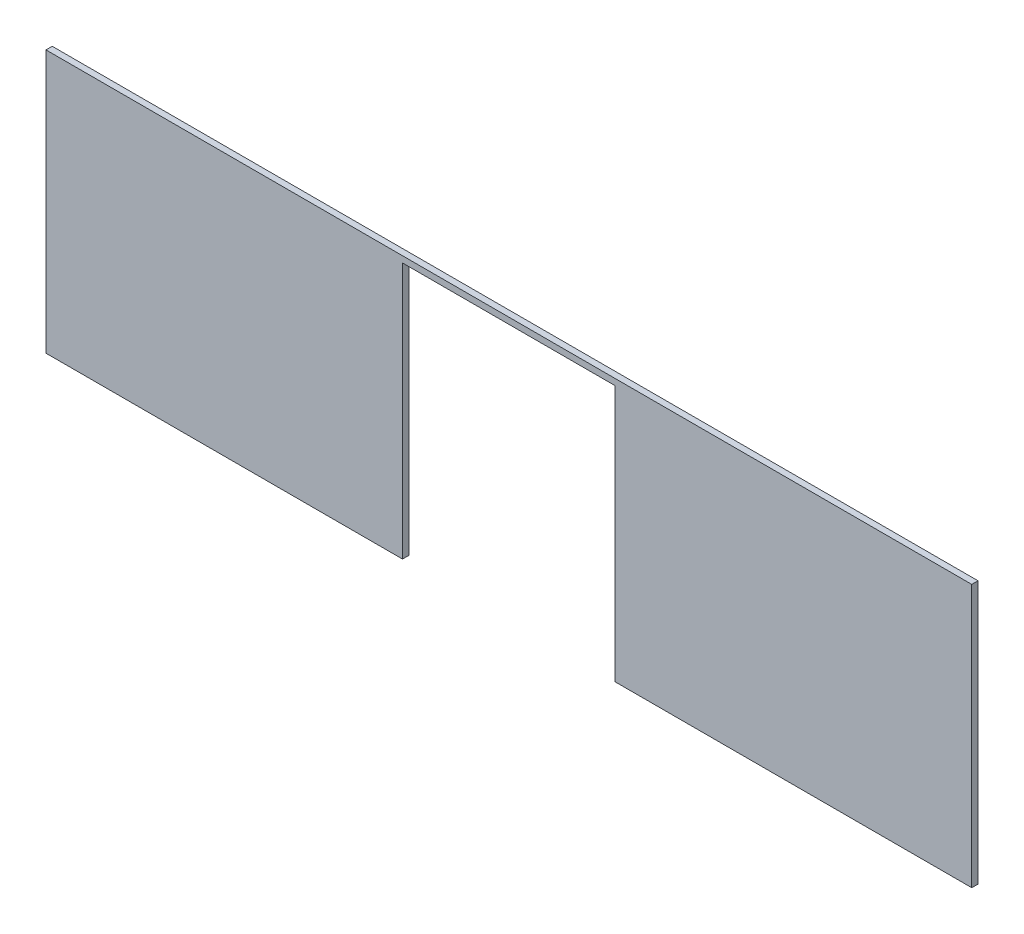
SolidWorks part; units mm, degrees
ref_plane "Front Plane" through (0, 0, 0) normal (0, 0, 1) x (1, 0, 0)
ref_plane "Top Plane" through (0, 0, 0) normal (0, 1, 0) x (1, 0, 0)
ref_plane "Right Plane" through (0, 0, 0) normal (1, 0, 0) x (0, 0, -1)
sketch "Sketch1" plane through (0, 0, 0) normal (0, 0, 1) x (1, 0, 0)
  line L1 (-234.95, -66.675) -> (234.95, -66.675)
  line L2 (-234.95, -66.675) -> (-234.95, 66.675)
  line L3 (-234.95, 66.675) -> (234.95, 66.675)
  line L4 (234.95, -66.675) -> (234.95, 66.675)
  line L5 (-234.95, -66.675) -> (234.95, 66.675) construction
  line L6 (-234.95, 66.675) -> (234.95, -66.675) construction
  point P0 (0, 0)
  dimension "D1" = 469.9
  dimension "D2" = 133.35
extrude "Boss-Extrude1" add sketch "Sketch1" along normal blind 3.175
sketch "Sketch2" plane through (0, 0, 3.175) normal (0, 0, 1) x (1, 0, 0)
  line L0 (-53.975, -66.675) -> (53.975, -66.675)
  line L1 (-234.95, -66.675) -> (234.95, -66.675) construction
  line L2 (53.975, -66.675) -> (53.975, 63.5)
  line L3 (53.975, 63.5) -> (-53.975, 63.5)
  line L5 (-53.975, -66.675) -> (-53.975, 63.5)
  point P10 (0, -66.675)
  dimension "D1" = 53.975
  dimension "D2" = 130.175
extrude "Cut-Extrude1" cut sketch "Sketch2" against normal blind 3.175 contours L3 L5 L0 L2
